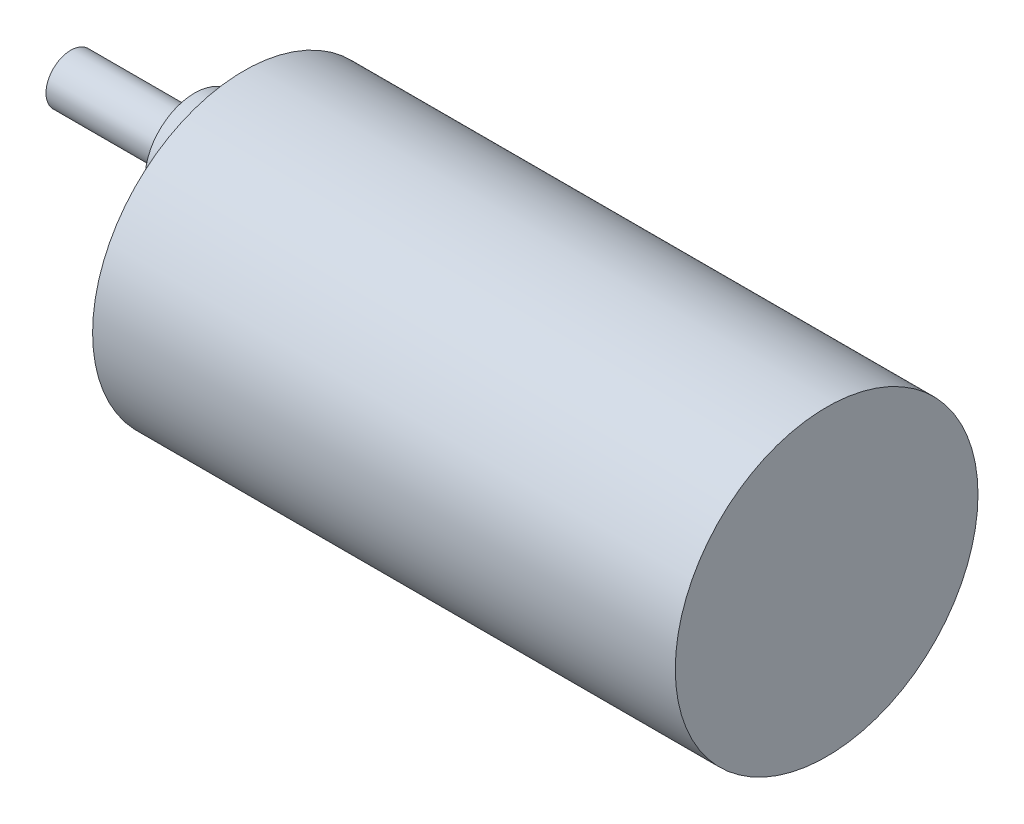
SolidWorks part; units mm, degrees
ref_plane "Plan de face" through (0, 0, 0) normal (0, 0, 1) x (1, 0, 0)
ref_plane "Plan de dessus" through (0, 0, 0) normal (0, 1, 0) x (1, 0, 0)
ref_plane "Plan de droite" through (0, 0, 0) normal (1, 0, 0) x (0, 0, -1)
sketch "Esquisse1" plane through (0, 0, 0) normal (1, 0, 0) x (0, 0, -1)
  circle A0 centre (0, 0) radius 18.35
  dimension "D1" = 36.7
extrude "Boss.-Extru.1" add sketch "Esquisse1" along normal blind 70.64 contours A0
sketch "Esquisse11" plane through (0, 0, 0) normal (-1, 0, 0) x (0, 0, 1)
  circle A0 centre (0, 0) radius 15.5 construction
  circle A1 centre (0, -15.5) radius 1.6
  circle A2 centre (-7.75, -13.4234) radius 1.6
  circle A4 centre (-15.5, 0) radius 1.6
  circle A5 centre (-13.4234, 7.75) radius 1.6
  circle A6 centre (-7.75, 13.4234) radius 1.6
  circle A8 centre (7.75, 13.4234) radius 1.6
  circle A9 centre (13.4234, 7.75) radius 1.6
  circle A10 centre (15.5, 0) radius 1.6
  circle A12 centre (7.75, -13.4234) radius 1.6
  circle A13 centre (13.4234, -7.75) radius 1.6 [skipped]
  circle A14 centre (-13.4234, -7.75) radius 1.6 [skipped]
  circle A15 centre (0, 15.5) radius 1.6 [skipped]
  point P30 (0, 0)
  dimension "D1" = 31
  dimension "D2" = 3.2
  dimension "D3" = 12
extrude "Enlèv. mat.-Extru.1" cut sketch "Esquisse11" against normal blind 10
sketch "Esquisse12" plane through (0, 0, 0) normal (-1, 0, 0) x (0, 0, 1)
  line L0 (0, 18.35) -> (0, -18.35) construction
  circle A0 centre (0, 0) radius 18.35 construction
  circle A1 centre (0, 7) radius 3
  dimension "D2" = 6
  dimension "D1" = 7
extrude "Boss.-Extru.2" add sketch "Esquisse12" along normal blind 21
sketch "Esquisse13" plane through (0, 0, 0) normal (-1, 0, 0) x (0, 0, 1)
  circle A0 centre (0, 7) radius 6
  dimension "D1" = 12
extrude "Boss.-Extru.3" add sketch "Esquisse13" along normal blind 6
sketch "Esquisse14" plane through (-21, 0, 0) normal (-1, 0, 0) x (0, 0, 1)
  line L0 (-1.3077, 4.3) -> (1.3077, 4.3)
  circle A0 centre (0, 7) radius 3 construction
  arc A1 (-1.3077, 4.3) -> (1.3077, 4.3) centre (0, 7) ccw
  point P6 (0, 10)
  dimension "D1" = 5.7
extrude "Enlèv. mat.-Extru.2" cut sketch "Esquisse14" against normal blind 11.8
